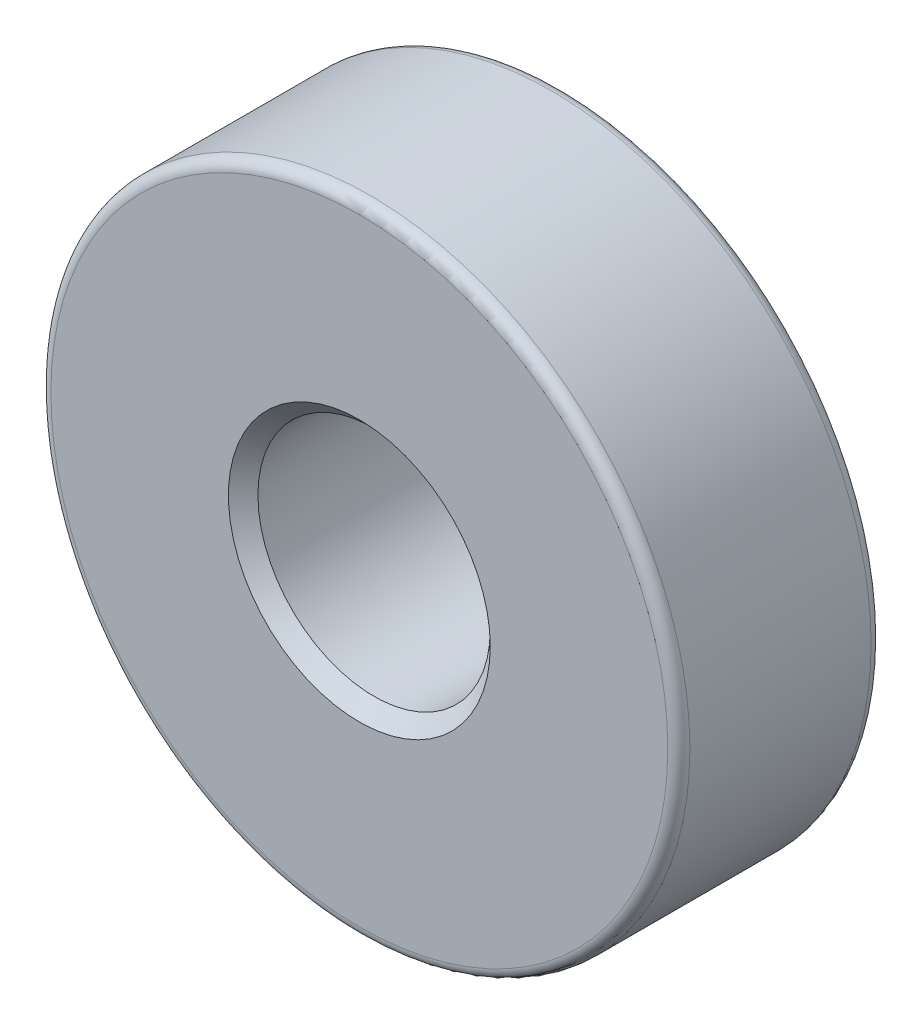
SolidWorks part; units mm, degrees
ref_plane "Front Plane" through (0, 0, 0) normal (0, 0, 1) x (1, 0, 0)
ref_plane "Top Plane" through (0, 0, 0) normal (0, 1, 0) x (1, 0, 0)
ref_plane "Right Plane" through (0, 0, 0) normal (1, 0, 0) x (0, 0, -1)
sketch "Sketch1" plane through (0, 0, 0) normal (0, 0, 1) x (1, 0, 0)
  circle A0 centre (0, 0) radius 4
  circle A1 centre (0, 0) radius 11
  dimension "D1" = 8
  dimension "D2" = 22
extrude "Boss-Extrude1" add sketch "Sketch1" along normal blind 7
fillet "Fillet1" radius 0.381 2 edges at (11, 0, 0) (11, 0, 7)
chamfer "Chamfer1" distance 0.508 angle 45 2 edges at (4, 0, 0) (4, 0, 7)
